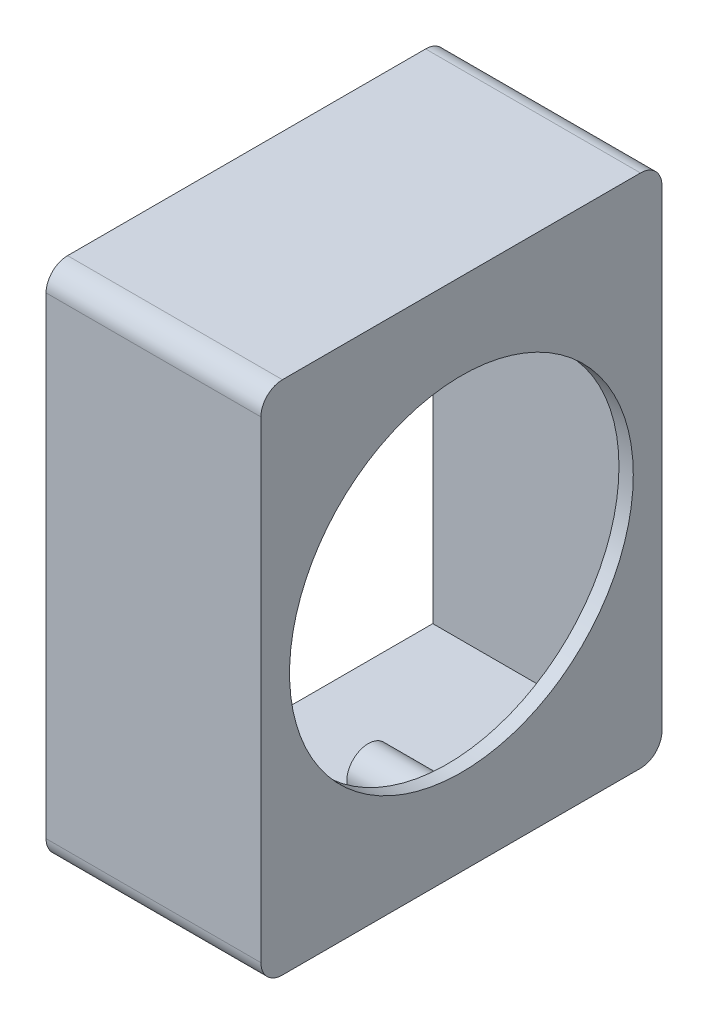
SolidWorks part; units mm, degrees
ref_plane "Front Plane" through (0, 0, 0) normal (1, 0, 0) x (0, 1, 0)
ref_plane "Top Plane" through (0, 0, 0) normal (0, 0, 1) x (0, 1, 0)
ref_plane "Right Plane" through (0, 0, 0) normal (0, 1, 0) x (-1, 0, 0)
sketch "Sketch1" plane through (0, 0, 0) normal (1, 0, 0) x (0, 1, 0)
  line L1 (-18, 17) -> (18, 17)
  line L2 (-18, 17) -> (-18, -17)
  line L3 (-18, -17) -> (18, -17)
  line L4 (18, 17) -> (18, -17)
  line L5 (-18, 17) -> (18, -17) construction
  line L6 (-18, -17) -> (18, 17) construction
  line L7 (-16, -13) -> (16, -13)
  line L8 (-16, -13) -> (-16, -15)
  line L9 (-16, -15) -> (16, -15)
  line L10 (16, -13) -> (16, -15)
  circle A0 centre (0, 3) radius 12
  point P0 (0, 0)
  dimension "D8" = 18
  dimension "D1" = 36
  dimension "D2" = 34
  dimension "D3" = 32
  dimension "D4" = 2
  dimension "D5" = 2
  dimension "D6" = 2
  dimension "D7" = 14
extrude "Boss-Extrude6" add sketch "Sketch1" along normal blind 1 contours L2 L1 L4 L3
sketch "Sketch7" plane through (1, 0, 0) normal (1, 0, 0) x (0, 1, 0)
  line L0 (-18, 17) -> (18, 17) construction
  line L1 (-18, 17) -> (-18, -17) construction
  circle A0 centre (0, 3) radius 12
  dimension "D1" = 14
  dimension "D2" = 18
extrude "Cut-Extrude1" cut sketch "Sketch7" against normal blind 1
sketch "Sketch8" plane through (0, 0, 0) normal (1, 0, 0) x (0, 1, 0)
  line L0 (-18, 17) -> (-18, -17) construction
  line L1 (-16, -11) -> (16, -11)
  line L2 (-16, -11) -> (-16, -13)
  line L3 (-16, -13) -> (16, -13)
  line L4 (16, -11) -> (16, -13)
  line L5 (-18, -17) -> (18, -17) construction
  dimension "D1" = 32
  dimension "D2" = 2
  dimension "D3" = 4
  dimension "D4" = 2
sketch "Sketch9" plane through (1, 0, 0) normal (1, 0, 0) x (0, 0, -1)
  line L0 (17, -18) -> (-17, -18)
  line L1 (-17, -18) -> (-17, 18)
  line L2 (-17, 18) -> (17, 18)
extrude "Extrude-Thin1" add sketch "Sketch9" against normal blind 15 thin
sketch "Sketch10" plane through (1, 0, 0) normal (1, 0, 0) x (0, 0, -1)
  line L1 (11, -24.0569) -> (17.4669, -24.0569)
  line L2 (11, -24.0569) -> (11, 24.0052)
  line L3 (11, 24.0052) -> (17.4669, 24.0052)
  line L4 (17.4669, -24.0569) -> (17.4669, 24.0052)
  circle A0 centre (-3, 0) radius 12 construction
  dimension "D1" = 14
extrude "Cut-Extrude2" cut sketch "Sketch10" against normal through all
sketch "Sketch11" plane through (0, 0, 0) normal (1, 0, 0) x (0, 1, 0)
  line L0 (-18, -11) -> (18, -11)
extrude "Extrude-Thin2" add sketch "Sketch11" against normal blind 14 thin thin type one direction reverse wall 1
fillet "Fillet3" radius 1.5 4 edges at (-6.5, -18, 17) (-6.5, 18, 17) (-6.5, -18, -11) (-6.5, 18, -11)
sketch "Sketch12" plane through (0, 0, 0) normal (1, 0, 0) x (0, 1, 0)
  line L0 (-17, 16) -> (-17, -10) construction
  line L1 (-17, -10) -> (17, -10) construction
  circle A0 centre (-14.5, 3.5) radius 1.5
  dimension "D1" = 2.5
  dimension "D2" = 3
  dimension "D3" = 13.5
extrude "Boss-Extrude7" add sketch "Sketch12" against normal blind 5
sketch "Sketch13" plane through (-5, 0, 0) normal (-1, 0, 0) x (0, -1, 0)
  circle A0 centre (14.5, 3.5) radius 1
extrude "Cut-Extrude3" cut sketch "Sketch13" against normal blind 5
mirror "Mirror1" about plane through (0, 0, 0) normal (0, 1, 0) of "Boss-Extrude7", "Cut-Extrude3"
